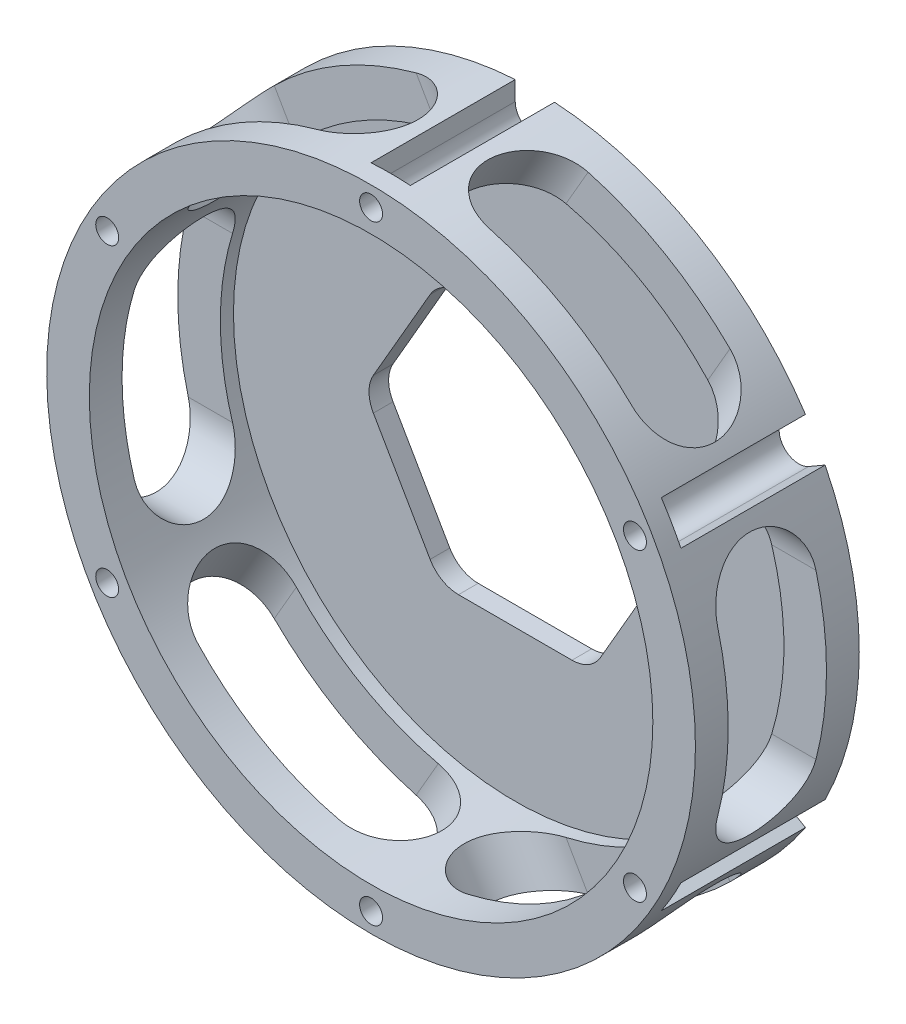
SolidWorks part; units mm, degrees
material "ABS"
ref_plane "Спереди" through (0, 0, 0) normal (0, 0, 1) x (1, 0, 0)
ref_plane "Сверху" through (0, 0, 0) normal (0, 1, 0) x (1, 0, 0)
ref_plane "Справа" through (0, 0, 0) normal (1, 0, 0) x (0, 0, -1)
sketch "Эскиз1" plane through (0, 0, 0) normal (0, 0, 1) x (1, 0, 0)
  line L0 (0, 0) -> (0, 46.5) construction
  circle A0 centre (0, 0) radius 50 construction
  circle A1 centre (0, 0) radius 43
  circle A2 centre (0, 0) radius 49.5
  circle A3 centre (0, 0) radius 46.5 construction
  circle A4 centre (0, 46.5) radius 1.75
  circle A5 centre (40.2702, 23.25) radius 1.75
  circle A6 centre (40.2702, -23.25) radius 1.75
  circle A7 centre (0, -46.5) radius 1.75
  circle A8 centre (-40.2702, -23.25) radius 1.75
  circle A9 centre (-40.2702, 23.25) radius 1.75
  point P23 (0, 0)
  dimension "D1" = 100
  dimension "D5" = 3.5
  dimension "D2" = 7
  dimension "D3" = 0.5
  dimension "D4" = 3.5
  dimension "D6" = 6
extrude "Бобышка-Вытянуть1" add sketch "Эскиз1" along normal blind 25
sketch "Эскиз2" plane through (0, 0, 0) normal (1, 0, 0) x (0, 0, -1)
  line L0 (0, 0) -> (-25, 0) construction
  line L1 (-25, 49.5) -> (-25, -49.5) construction
  line L2 (-12.5, 12.5) -> (-12.5, -12.5) construction
  line L3 (-5, 12.5) -> (-5, -12.5)
  line L4 (-20, 12.5) -> (-20, -12.5)
  arc A0 (-5, 12.5) -> (-20, 12.5) centre (-12.5, 12.5) ccw
  arc A1 (-20, -12.5) -> (-5, -12.5) centre (-12.5, -12.5) ccw
  point P7 (-12.5, 0)
  dimension "D1" = 25
  dimension "D2" = 15
extrude "Вырез-Вытянуть1" cut sketch "Эскиз2" against normal blind 59
pattern_circular "Круговой массив1" count 6 over 360 about axis through (0, 0, 25) along (0, 0, -1) of "Вырез-Вытянуть1"
sketch "Эскиз3" plane through (0, 0, 0) normal (0, 0, -1) x (-1, 0, 0)
  circle A0 centre (0, 0) radius 44.0458
extrude "Бобышка-Вытянуть2" add sketch "Эскиз3" against normal blind 3
sketch "Эскиз4" plane through (0, 0, 0) normal (0, 0, -1) x (-1, 0, 0)
  line L0 (0, 46.5) -> (0, 53.5027) construction
  line L1 (-3, 46.5) -> (-3, 53.5027)
  line L2 (3, 46.5) -> (3, 53.5027)
  line L3 (-40.2702, 23.25) -> (-46.3347, 26.7514) construction
  line L4 (-41.7702, 20.6519) -> (-47.8347, 24.1533)
  line L5 (-38.7702, 25.8481) -> (-44.8347, 29.3494)
  line L6 (-40.2702, -23.25) -> (-46.3347, -26.7514) construction
  line L7 (-38.7702, -25.8481) -> (-44.8347, -29.3494)
  line L8 (-41.7702, -20.6519) -> (-47.8347, -24.1533)
  line L9 (0, -46.5) -> (0, -53.5027) construction
  line L10 (3, -46.5) -> (3, -53.5027)
  line L11 (-3, -46.5) -> (-3, -53.5027)
  line L12 (40.2702, -23.25) -> (46.3347, -26.7514) construction
  line L13 (41.7702, -20.6519) -> (47.8347, -24.1533)
  line L14 (38.7702, -25.8481) -> (44.8347, -29.3494)
  line L15 (40.2702, 23.25) -> (46.3347, 26.7514) construction
  line L16 (38.7702, 25.8481) -> (44.8347, 29.3494)
  line L17 (41.7702, 20.6519) -> (47.8347, 24.1533)
  arc A0 (-3, 46.5) -> (3, 46.5) centre (0, 46.5) ccw
  arc A1 (3, 53.5027) -> (-3, 53.5027) centre (0, 53.5027) ccw
  arc A2 (-41.7702, 20.6519) -> (-38.7702, 25.8481) centre (-40.2702, 23.25) ccw
  arc A3 (-44.8347, 29.3494) -> (-47.8347, 24.1533) centre (-46.3347, 26.7514) ccw
  arc A4 (-38.7702, -25.8481) -> (-41.7702, -20.6519) centre (-40.2702, -23.25) ccw
  arc A5 (-47.8347, -24.1533) -> (-44.8347, -29.3494) centre (-46.3347, -26.7514) ccw
  arc A6 (3, -46.5) -> (-3, -46.5) centre (0, -46.5) ccw
  arc A7 (-3, -53.5027) -> (3, -53.5027) centre (0, -53.5027) ccw
  arc A8 (41.7702, -20.6519) -> (38.7702, -25.8481) centre (40.2702, -23.25) ccw
  arc A9 (44.8347, -29.3494) -> (47.8347, -24.1533) centre (46.3347, -26.7514) ccw
  arc A10 (38.7702, 25.8481) -> (41.7702, 20.6519) centre (40.2702, 23.25) ccw
  arc A11 (47.8347, 24.1533) -> (44.8347, 29.3494) centre (46.3347, 26.7514) ccw
  point P2 (0, 50.0014)
  point P13 (-43.3024, 25.0007)
  point P20 (-43.3024, -25.0007)
  point P27 (0, -50.0014)
  point P34 (43.3024, -25.0007)
  point P41 (43.3024, 25.0007)
  point P46 (0, 0)
  dimension "D1" = 6
  dimension "D3" = 7.0027
  dimension "D2" = 6
extrude "Вырез-Вытянуть3" cut sketch "Эскиз4" against normal blind 22
sketch "Эскиз5" plane through (0, 0, 0) normal (0, 0, -1) x (-1, 0, 0)
  line L1 (8.6603, 20) -> (-8.6603, 20)
  line L2 (-12.9904, 17.5) -> (-21.6506, 2.5)
  line L3 (-21.6506, -2.5) -> (-12.9904, -17.5)
  line L4 (-8.6603, -20) -> (8.6603, -20)
  line L5 (12.9904, -17.5) -> (21.6506, -2.5)
  line L6 (21.6506, 2.5) -> (12.9904, 17.5)
  circle A0 centre (0, 0) radius 20 construction
  arc A1 (-21.6506, 2.5) -> (-21.6506, -2.5) centre (-17.3205, 0) ccw
  arc A2 (-12.9904, -17.5) -> (-8.6603, -20) centre (-8.6603, -15) ccw
  arc A3 (8.6603, -20) -> (12.9904, -17.5) centre (8.6603, -15) ccw
  arc A4 (21.6506, -2.5) -> (21.6506, 2.5) centre (17.3205, 0) ccw
  arc A5 (8.6603, 20) -> (12.9904, 17.5) centre (8.6603, 15) cw
  arc A6 (-8.6603, 20) -> (-12.9904, 17.5) centre (-8.6603, 15) ccw
  dimension "D2" = 5
  dimension "D1" = 40
extrude "Вырез-Вытянуть4" cut sketch "Эскиз5" against normal blind 10
